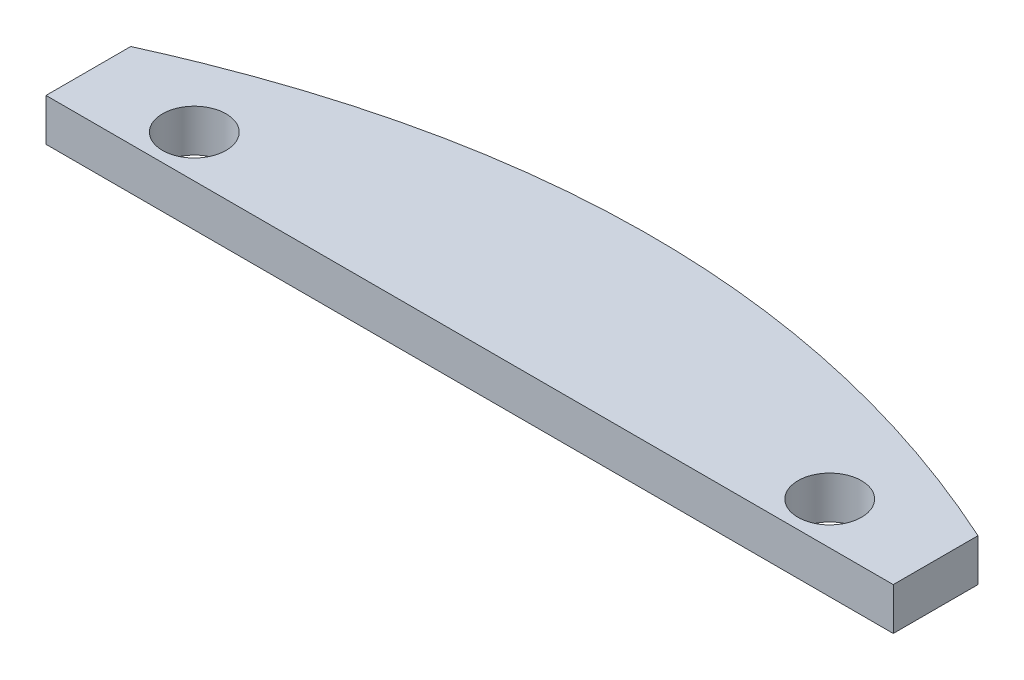
SolidWorks part; units mm, degrees
ref_plane "Front Plane" through (0, 0, 0) normal (0, 0, 1) x (1, 0, 0)
ref_plane "Top Plane" through (0, 0, 0) normal (0, 1, 0) x (1, 0, 0)
ref_plane "Right Plane" through (0, 0, 0) normal (1, 0, 0) x (0, 0, -1)
sketch "Sketch1" plane through (0, 0, 0) normal (0, 1, 0) x (1, 0, 0)
  line L0 (3.9243, 6.0047) -> (3.9243, 29.1726) construction
  line L2 (-16.0757, 6.0047) -> (-16.0757, 2.0047)
  line L3 (-16.0757, 2.0047) -> (23.9243, 2.0047)
  line L4 (23.9243, 6.0047) -> (23.9243, 2.0047)
  line L5 (-16.0757, 4.0047) -> (4.8205, 4.0047) construction
  circle A0 centre (-11.0757, 4.0047) radius 1.5
  circle A1 centre (18.9243, 4.0047) radius 1.5
  spline S0 degree 2 poles (-16.0757, 6.0047) (3.9243, 15.0827) (23.9243, 6.0047) knots 0 0 0 1 1 1
  dimension "D4" = 15
  dimension "D1" = 40
  dimension "D2" = 4
  dimension "D3" = 0
  dimension "D5" = 0
extrude "Boss-Extrude1" add sketch "Sketch1" along normal blind 2
